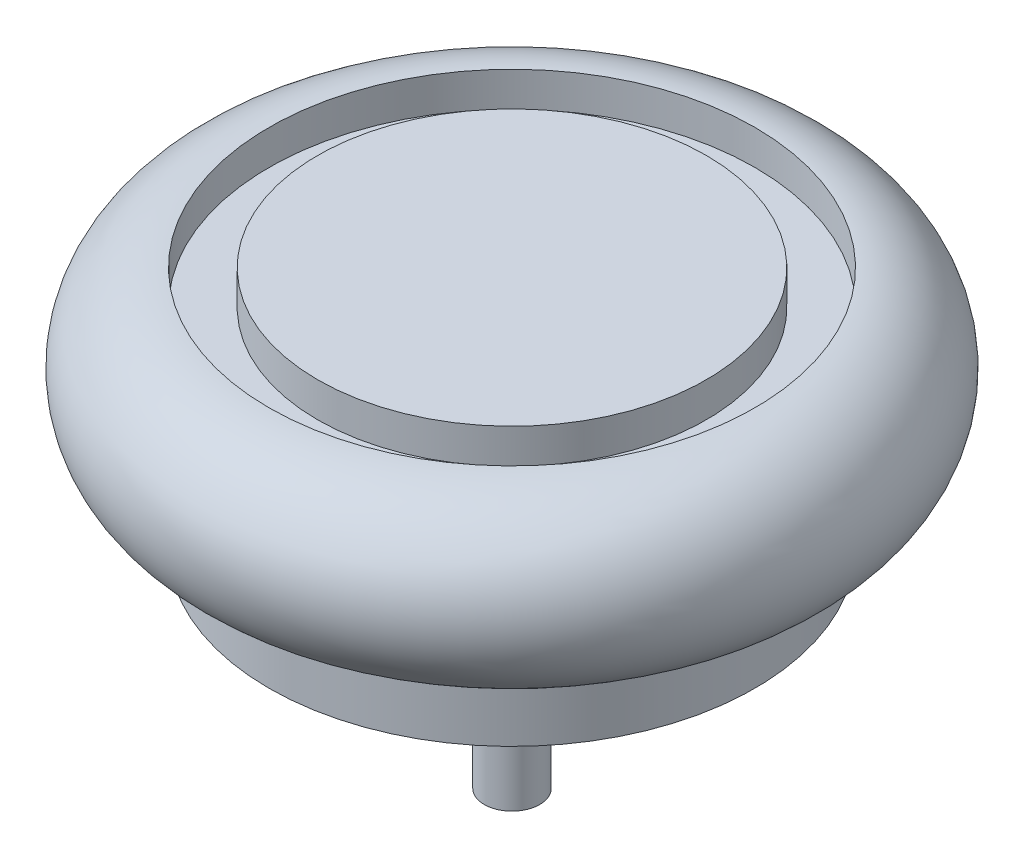
SolidWorks part; units mm, degrees
ref_plane "Front Plane" through (0, 0, 0) normal (1, 0, 0) x (0, 1, 0)
ref_plane "Top Plane" through (0, 0, 0) normal (0, 0, 1) x (0, 1, 0)
ref_plane "Right Plane" through (0, 0, 0) normal (0, 1, 0) x (-1, 0, 0)
sketch "Sketch2" plane through (0, 0, 0) normal (1, 0, 0) x (0, 1, 0)
  line L0 (0, 0) -> (0, 70)
  line L1 (50, 70) -> (40, 70)
  line L2 (40, 70) -> (40, 56)
  line L3 (40, 56) -> (50, 56)
  line L4 (50, 56) -> (50, 0)
  line L5 (50, 0) -> (0, 0)
  arc A0 (50, 70) -> (0, 70) centre (25, 70) ccw
  dimension "D1" = 25
  dimension "D2" = 70
  dimension "D3" = 50
  dimension "D4" = 14
  dimension "D5" = 10
revolve "Revolve1" add sketch "Sketch2" angle 360 about L5
sketch "Sketch3" plane through (0, 0, 0) normal (0, -1, 0) x (1, 0, 0)
  circle A0 centre (0, 0) radius 70
  circle A1 centre (0, 0) radius 40
  dimension "D1" = 140
  dimension "D2" = 80
extrude "Boss-Extrude2" add sketch "Sketch3" along normal blind 20
sketch "Sketch4" plane through (0, 0, 0) normal (0, -1, 0) x (1, 0, 0)
  circle A0 centre (0, 0) radius 8
  dimension "D1" = 16
extrude "Boss-Extrude3" add sketch "Sketch4" along normal blind 80
